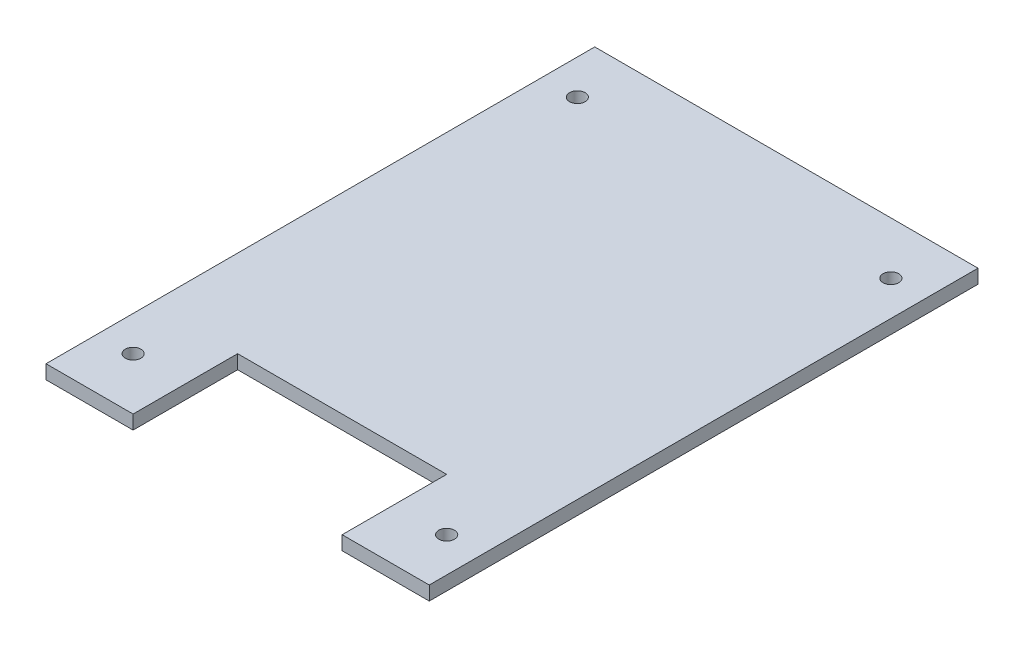
SolidWorks part; units mm, degrees
material "Acrílico (médio-alto impacto)"
ref_plane "Plano frontal" through (0, 0, 0) normal (0, 0, 1) x (1, 0, 0)
ref_plane "Plano superior" through (0, 0, 0) normal (0, 1, 0) x (1, 0, 0)
ref_plane "Plano direito" through (0, 0, 0) normal (1, 0, 0) x (0, 0, -1)
sketch "Esboço1" plane through (0, 0, 0) normal (0, 1, 0) x (1, 0, 0)
  line L0 (30, -78.75) -> (55, -78.75)
  line L1 (-55, -78.75) -> (-30, -78.75)
  line L2 (-55, -78.75) -> (-55, 78.75)
  line L3 (-55, 78.75) -> (55, 78.75)
  line L4 (55, -78.75) -> (55, 78.75)
  line L5 (-55, -78.75) -> (55, 78.75) construction
  line L6 (-55, 78.75) -> (55, -78.75) construction
  line L8 (-30, -78.75) -> (-30, -48.75)
  line L9 (-30, -48.75) -> (30, -48.75)
  line L10 (30, -78.75) -> (30, -48.75)
  point P0 (0, 0)
  point P10 (0, -48.75)
  point P11 (55, 0)
  dimension "D1" = 60
  dimension "D2" = 110
  dimension "D3" = 157.5
  dimension "D4" = 30
extrude "Ressalto-extrusão1" add sketch "Esboço1" along normal blind 4
hole_wizard "Furo com folga de M41" positions "Esboço2" profile "Esboço3" hole size "M4" standard "ISO" end condition through all
sketch "Esboço2" plane through (0, 4, 0) normal (0, 1, 0) x (1, 0, 0)
  line L0 (-55, 78.75) -> (-55, -78.75) construction
  line L1 (55, -78.75) -> (55, 78.75) construction
  line L2 (-55, -78.75) -> (-30, -78.75) construction
  line L3 (55, 78.75) -> (-55, 78.75) construction
  point P0 (-45, 63.75)
  point P2 (45, 63.75)
  point P4 (45, -63.75)
  point P6 (-45, -63.75)
  dimension "D1" = 10
  dimension "D2" = 10
  dimension "D3" = 15
  dimension "D4" = 15
sketch "Esboço3" plane through (-45, 4, -63.75) normal (1, 0, 0) x (0, 0, 1)
  line L0 (0, 0) -> (0, 4)
  line L1 (0, 4) -> (2.25, 4)
  line L2 (2.25, 4) -> (2.25, 0)
  line L5 (2.25, 0) -> (0, 0)
  line L11 (0, -6.35) -> (0, 107.95) construction
  dimension "Thru Hole Dia." = 4.5
  dimension "Thru Hole Depth" = 4
